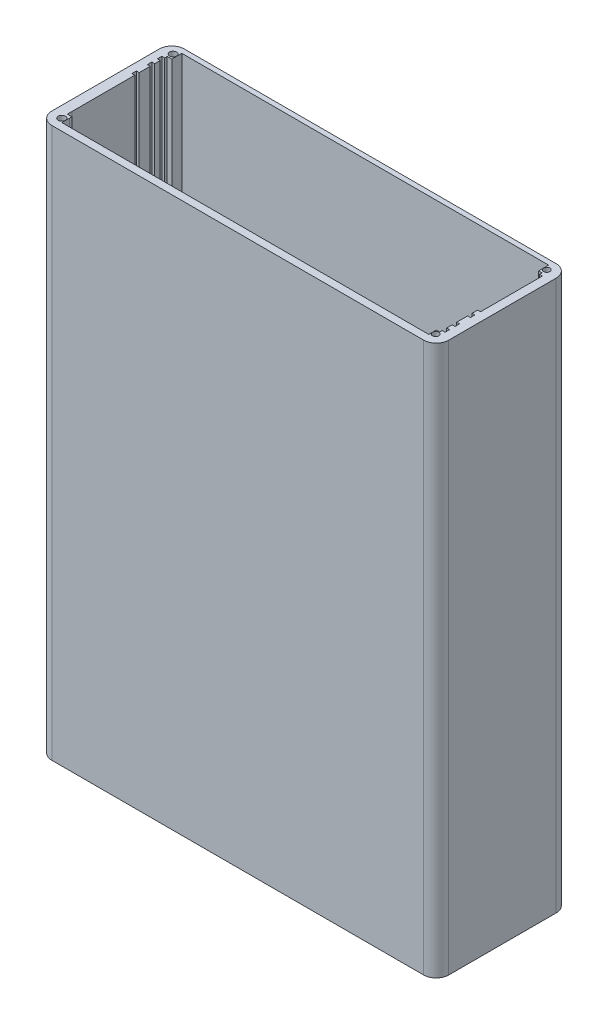
SolidWorks part; units mm, degrees
material "3003-O, Rod (SS)"
ref_plane "Front Plane" through (0, 0, 0) normal (0, 0, 1) x (1, 0, 0)
ref_plane "Top Plane" through (0, 0, 0) normal (0, 1, 0) x (1, 0, 0)
ref_plane "Right Plane" through (0, 0, 0) normal (1, 0, 0) x (0, 0, -1)
sketch "Sketch1" plane through (0, 0, 0) normal (0, 1, 0) x (1, 0, 0)
  line L0 (-99.1786, 19.6345) -> (-99.1786, -20.7676) construction
  line L1 (-105.1786, -38) -> (53.6214, -38)
  line L2 (-105.1786, -38) -> (-105.1786, 15)
  line L3 (-105.1786, 15) -> (53.6214, 15)
  line L4 (53.6214, -38) -> (53.6214, 15)
  line L5 (-102.15, 13) -> (50.15, 13) construction
  line L6 (-102.15, 13) -> (-102.15, -35) construction
  line L7 (-101, 13) -> (49, 13) construction
  line L8 (-101, 13) -> (-101, -35) construction
  line L9 (-101, -35) -> (49, -35) construction
  line L10 (49, 13) -> (49, -35) construction
  line L11 (-102.15, -35) -> (50.15, -35) construction
  line L12 (50.15, 13) -> (50.15, -35) construction
  line L13 (49, -31) -> (49, -32)
  line L14 (49, -31) -> (50.15, -31)
  line L15 (-99.1861, -31) -> (-99.1861, -32)
  line L16 (-59.2264, 9) -> (-29.453, 9) construction
  line L17 (-101, 9) -> (-99.1786, 9)
  line L18 (50.15, -31) -> (50.15, -29.2)
  line L19 (50.15, -29.2) -> (49, -29.2)
  line L20 (49, -29.2) -> (49, -27)
  line L21 (49, -27) -> (50.15, -27)
  line L22 (-99.1786, 9) -> (-99.1786, 13)
  line L23 (50.15, -27) -> (50.15, -25.2)
  line L24 (50.15, -25.2) -> (49, -25.2)
  line L25 (-99.1861, -32) -> (-99.1786, -32)
  line L26 (-99.1861, -31) -> (-101.0068, -31)
  line L27 (-101.0068, -31) -> (-101.0068, -29.2)
  line L28 (-101.0068, -29.2) -> (-100.9974, -29.2)
  line L29 (-100.9974, -29.2) -> (-100.9974, -4)
  line L30 (-100.9974, -4) -> (-102.15, -4)
  line L31 (-102.15, -4) -> (-102.15, -2.2)
  line L32 (-102.15, -2.2) -> (-101, -2.2)
  line L33 (-101, 9) -> (-101, 8)
  line L34 (47.6214, 14.0751) -> (47.6214, -2.2) construction
  line L35 (-102.15, 13) -> (-99.1786, 9) construction
  line L36 (-57.7785, -32) -> (-24.4678, -32) construction
  line L37 (-99.1786, -32) -> (-99.1786, -35)
  line L38 (-101, 8) -> (-102.15, 8)
  line L39 (-102.15, 8) -> (-102.15, 6.2)
  line L40 (-102.15, 6.2) -> (-101, 6.2)
  line L41 (-101, 6.2) -> (-101, 4)
  line L42 (-101, 4) -> (-102.15, 4)
  line L43 (-102.15, 4) -> (-102.15, 2.2)
  line L44 (-102.15, 2.2) -> (-101, 2.2)
  line L45 (-101, 2.2) -> (-101, -2.2)
  line L46 (-102.15, -35) -> (-99.1786, -32) construction
  line L47 (49, -25.2) -> (49, -20.8)
  line L48 (49, -20.8) -> (50.15, -20.8)
  line L49 (50.15, -20.8) -> (50.15, -19)
  line L50 (50.15, -19) -> (49, -19)
  line L51 (49, -19) -> (49, -16.8)
  line L52 (49, -16.8) -> (50.15, -16.8)
  line L53 (50.15, -16.8) -> (50.15, 8)
  line L54 (50.15, 8) -> (49, 8)
  line L55 (49, 9) -> (49, 8)
  line L56 (49, 9) -> (47.6214, 9)
  line L57 (47.6214, 9) -> (47.6214, 13)
  line L58 (49, -32) -> (47.6214, -32)
  line L59 (47.6214, -32) -> (47.6214, -35)
  line L60 (47.6214, -35) -> (-99.1786, -35)
  line L61 (47.6214, 9) -> (50.15, 13) construction
  line L62 (47.6214, -32) -> (50.15, -35) construction
  line L63 (-99.1786, 13) -> (47.6214, 13)
  circle A0 centre (-100.6643, 11) radius 1.4
  circle A1 centre (48.8857, 11) radius 1.25
  circle A2 centre (-100.6643, -33.5) radius 1.45
  circle A3 centre (48.8857, -33.5) radius 1.25
  point P0 (0, 0)
  point P4 (0, 0)
  point P7 (0, 0)
  point P8 (0, 0)
  point P18 (49, -31)
  point P20 (49, -8)
  point P21 (50.15, -31)
  point P25 (-101, 9)
  point P27 (50.15, -29.2)
  point P28 (-49, 9)
  point P29 (50.15, -6.2)
  point P30 (49, -29.2)
  point P33 (49, -27)
  point P34 (50.15, -27)
  point P36 (-99.1786, 9)
  point P38 (50.15, -25.2)
  point P39 (-99.1786, 13)
  point P40 (49, -25.2)
  point P43 (-99.1861, -31)
  point P44 (-101.0068, -31)
  point P45 (-101.0068, -29.2)
  point P46 (-100.9974, -29.2)
  point P47 (-100.9974, -4)
  point P48 (-102.15, -4)
  point P49 (-102.15, -2.2)
  point P50 (-101, -2.2)
  point P62 (-100.6643, 11)
  point P63 (-100.6643, 11)
  point P65 (-99.1861, -32)
  point P66 (-101, 8)
  point P68 (-102.15, 8)
  point P69 (-50.15, 6.2)
  point P70 (-102.15, 6.2)
  point P71 (-101, 6.2)
  point P72 (-49, 6.2)
  point P73 (-101, 4)
  point P74 (-102.15, 4)
  point P75 (-102.15, 2.2)
  point P76 (-101, 2.2)
  point P82 (49, -20.8)
  point P86 (50.15, -20.8)
  point P87 (50.15, -19)
  point P88 (50.15, 4)
  point P89 (49, -19)
  point P90 (49, 4)
  point P91 (49, -16.8)
  point P92 (50.15, -16.8)
  point P93 (50.15, 6.2)
  point P94 (50.15, 8)
  point P95 (50.15, 8)
  point P96 (49, 8)
  point P105 (-49, -9)
  point P106 (-99.1786, -32)
  point P107 (-99.1786, -35)
  point P110 (-100.6643, -33.5)
  point P112 (-100.6643, -33.5)
  point P114 (49, 9)
  point P116 (47.6214, 9)
  point P117 (47.6214, 9)
  point P118 (47.6214, 13)
  point P122 (49, -32)
  point P123 (49, -9)
  point P124 (47.6214, -32)
  point P125 (47.6214, -35)
  point P129 (48.8857, 11)
  point P130 (48.8857, 11)
  point P131 (48.8857, -33.5)
  point P132 (48.8857, -33.5)
  dimension "D11" = 2.8
  dimension "D12" = 2.5
  dimension "D13" = 2.9
  dimension "D14" = 2.5
  dimension "D1" = 158.8
  dimension "D2" = 53
  dimension "D3" = 150
  dimension "D4" = 48
  dimension "D5" = 48
  dimension "D6" = 152.3
  dimension "D7" = 6
  dimension "D8" = 6
  dimension "D9" = 6
  dimension "D10" = 6
extrude "Boss-Extrude1" add sketch "Sketch1" along normal blind 220
fillet "Fillet1" radius 5 1 edges at (-105.1786, 110, -15)
fillet "Fillet2" radius 5 1 edges at (-105.1786, 110, 38)
fillet "Fillet3" radius 5 1 edges at (53.6214, 110, -15)
fillet "Fillet4" radius 5 1 edges at (53.6214, 110, 38)
